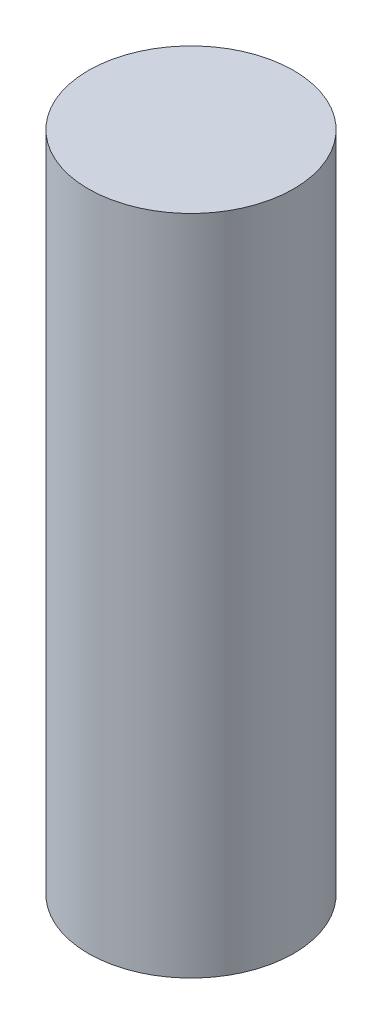
SolidWorks part; units mm, degrees
ref_plane "Front Plane" through (0, 0, 0) normal (0, 0, 1) x (1, 0, 0)
ref_plane "Top Plane" through (0, 0, 0) normal (0, 1, 0) x (1, 0, 0)
ref_plane "Right Plane" through (0, 0, 0) normal (1, 0, 0) x (0, 0, -1)
sketch "Sketch1" plane through (0, 0, 0) normal (0, 1, 0) x (1, 0, 0)
  circle A0 centre (0, 0) radius 1.55
extrude "Boss-Extrude1" add sketch "Sketch1" along normal blind 10
